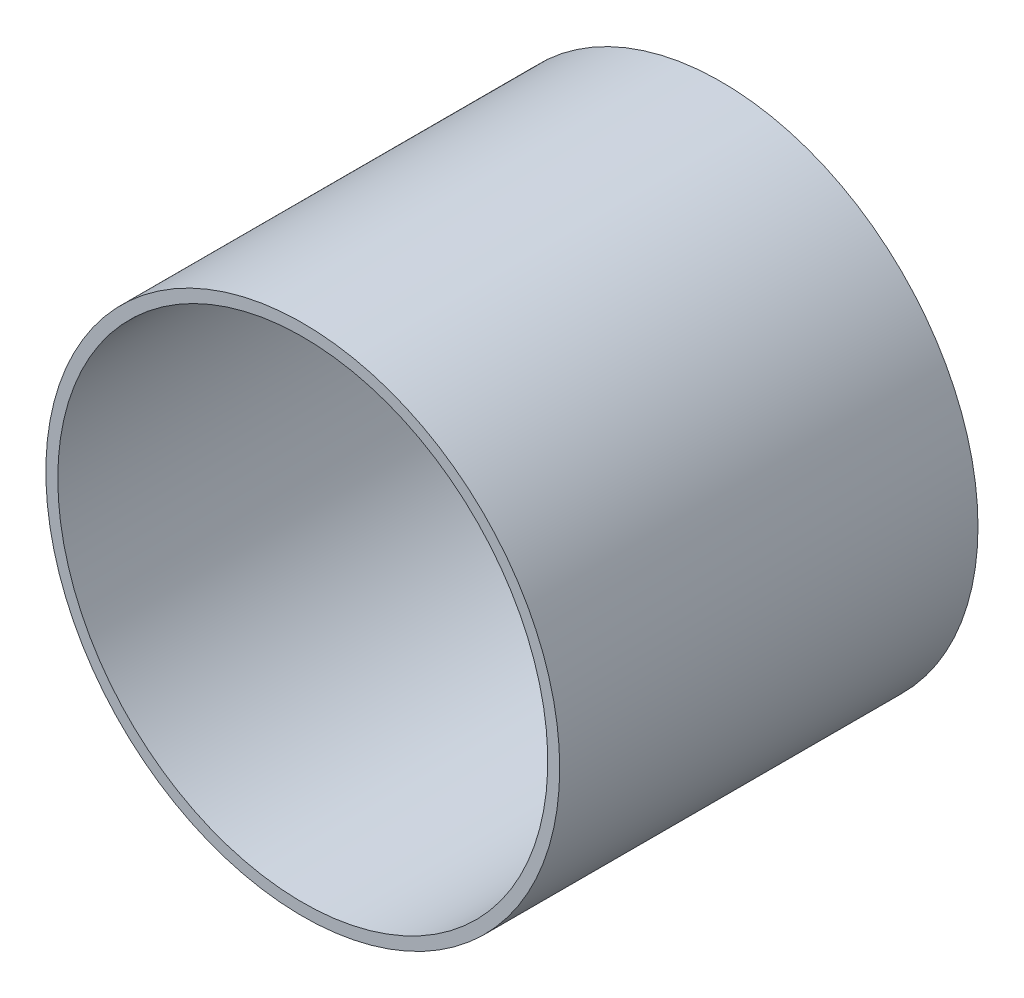
SolidWorks part; units mm, degrees
ref_plane "Front Plane" through (0, 0, 0) normal (0, 0, 1) x (1, 0, 0)
ref_plane "Top Plane" through (0, 0, 0) normal (0, 1, 0) x (1, 0, 0)
ref_plane "Right Plane" through (0, 0, 0) normal (1, 0, 0) x (0, 0, -1)
sketch "Sketch3" plane through (0, 0, 0) normal (0, 0, 1) x (1, 0, 0)
  circle A0 centre (0, 0) radius 215
  dimension "D1" = 430
extrude "Boss-Extrude2" add sketch "Sketch3" along normal blind 350
sketch "Sketch4" plane through (0, 0, 0) normal (0, 0, -1) x (-1, 0, 0)
  circle A0 centre (0, 0) radius 205
  circle A1 centre (0, 0) radius 215 construction
  dimension "D1" = 10
extrude "Cut-Extrude1" cut sketch "Sketch4" against normal blind 350
